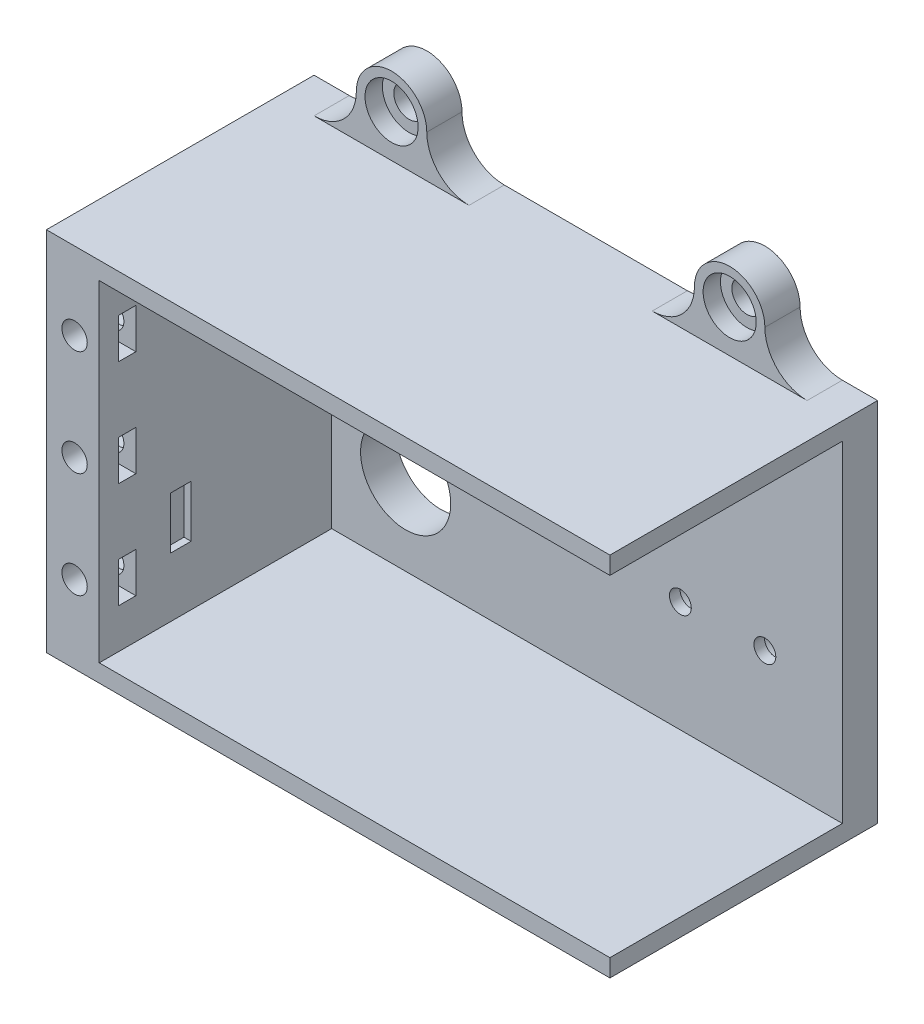
SolidWorks part; units mm, degrees
material "ABS"
ref_plane "Plan de face" through (0, 0, 0) normal (0, 0, 1) x (1, 0, 0)
ref_plane "Plan de dessus" through (0, 0, 0) normal (0, 1, 0) x (1, 0, 0)
ref_plane "Plan de droite" through (0, 0, 0) normal (1, 0, 0) x (0, 0, -1)
sketch "Esquisse3" plane through (0, 0, 0) normal (0, 0, 1) x (1, 0, 0)
  line L1 (-40, -26) -> (40, -26)
  line L2 (-40, -26) -> (-40, 26)
  line L3 (-40, 26) -> (40, 26)
  line L4 (40, -26) -> (40, 26)
  line L5 (-40, -26) -> (40, 26) construction
  line L6 (-40, 26) -> (40, -26) construction
  point P0 (0, 0)
  dimension "D1" = 80
  dimension "D2" = 52
extrude "Boss.-Extru.1" add sketch "Esquisse3" along normal blind 5 contours L3 L4 L1 L2
sketch "Esquisse4" plane through (0, 0, 5) normal (0, 0, 1) x (1, 0, 0)
  line L0 (-40, -26) -> (40, -26) construction
  line L1 (-40, -26) -> (-40, 26) construction
  circle A0 centre (-22, -12) radius 6.4
  dimension "D1" = 12.8
  dimension "D2" = 14
  dimension "D3" = 18
extrude "Enlèv. mat.-Extru.1" cut sketch "Esquisse4" against normal blind 10 contours A0
sketch "Esquisse5" plane through (0, 0, 5) normal (0, 0, 1) x (1, 0, 0)
  line L0 (40, -26) -> (40, 26) construction
  line L1 (-40, -26) -> (40, -26)
  line L3 (-32.5, -23.5) -> (40, -23.5)
  line L4 (40, -26) -> (40, -23.5)
  line L7 (-40, 26) -> (-40, -26)
  line L9 (-32.5, 23.5) -> (-32.5, -23.5)
  line L10 (-40, 26) -> (40, 26)
  line L12 (-32.5, 23.5) -> (40, 23.5)
  line L13 (40, 26) -> (40, 23.5)
  dimension "D1" = 7.5
  dimension "D2" = 2.5
  dimension "D3" = 2.5
extrude "Boss.-Extru.2" add sketch "Esquisse5" along normal blind 33
hole_wizard "Chambrage pour vis à tête ronde bombée M2.51" positions "Esquisse9" profile "Esquisse10" counterbore size "M2.5" standard "Ansi Metric" end condition up to next
sketch "Esquisse9" plane through (0, 0, 0) normal (0, 0, -1) x (-1, 0, 0)
  line L0 (40, 26) -> (-40, 26) construction
  line L1 (-40, -26) -> (-40, 26) construction
  point P0 (-17, 16.25)
  dimension "D1" = 9.75
  dimension "D2" = 23
sketch "Esquisse10" plane through (17, 16.25, 0) normal (1, 0, 0) x (0, 1, 0)
  line L0 (0, 0) -> (0, 5)
  line L1 (0, 5) -> (1.55, 5)
  line L3 (1.55, 5) -> (1.55, 3.5)
  line L4 (1.55, 3.5) -> (3, 3.5)
  line L5 (3, 3.5) -> (3, 0)
  line L7 (3, 0) -> (0, 0)
  line L11 (0, -6.35) -> (0, 107.95) construction
  dimension "Diamètre du perçage jusqu'au prochain" = 3.1
  dimension "Profondeur du perçage jusqu'au prochain" = 5
  dimension "Diamètre du chambrage" = 6
  dimension "Profondeur du chambrage" = 3.5
pattern_linear "Répétition linéaire1" count 2 spacing 12 along (1, 0, 0) count 2 spacing 24 along (0, -1, 0) of "Chambrage pour vis à tête ronde bombée M2.51"
sketch "Esquisse11" plane through (-40, 0, 0) normal (-1, 0, 0) x (0, 0, 1)
  line L0 (38, 26) -> (38, -26) construction
  line L1 (35.3, 17.85) -> (32.8, 17.85)
  line L2 (35.3, 17.85) -> (35.3, 12.15)
  line L3 (35.3, 12.15) -> (32.8, 12.15)
  line L4 (32.8, 17.85) -> (32.8, 12.15)
  line L14 (36.4917, 15) -> (30.8768, 15) construction
  line L15 (38, 26) -> (0, 26) construction
  dimension "D1" = 2.7
  dimension "D2" = 2.5
  dimension "D3" = 5.7
  dimension "D4" = 11
  dimension "D5" = 2.85
extrude "Enlèv. mat.-Extru.2" cut sketch "Esquisse11" against normal up to next
pattern_linear "Répétition linéaire2" count 3 spacing 15 along (0, -1, 0) of "Enlèv. mat.-Extru.2"
hole_wizard "Dégagement M31" positions "Esquisse13" profile "Esquisse15" hole size "M3" standard "Ansi Metric"
sketch "Esquisse13" plane through (0, 0, 38) normal (0, 0, 1) x (1, 0, 0)
  point P0 (-36, 15)
sketch "Esquisse15" plane through (-36, 15, 38) normal (1, 0, 0) x (0, -1, 0)
  line L0 (0, 0) -> (0, 7.4315)
  line L1 (0, 7.4315) -> (1.8, 6.35)
  line L2 (1.8, 6.35) -> (1.8, 0)
  line L5 (1.8, 0) -> (0, 0)
  line L10 (0, 7.4315) -> (-1.8, 6.35) construction
  line L11 (0, -6.35) -> (0, 107.95) construction
  dimension "Diamètre du perçage" = 3.6
  dimension "Profondeur du perçage" = 6.35
  dimension "Angle de pointe" = 118
pattern_linear "Répétition linéaire3" count 3 spacing 15 along (0, -1, 0) of "Dégagement M31"
sketch "Esquisse16" plane through (0, 0, 0) normal (0, 0, -1) x (-1, 0, 0)
  line L0 (-24, 52.4996) -> (-24, -58.7547) construction
  line L1 (24, 64.8334) -> (24, -50.5694) construction
  line L2 (40, 26) -> (-40, 26) construction
  line L3 (40, -26) -> (-40, -26) construction
  line L4 (-40, -26) -> (-40, 26) construction
  line L5 (40, -26) -> (40, 26) construction
  line L6 (-35, 26) -> (-13, 26)
  line L7 (13, 26) -> (35, 26)
  line L8 (-35, -26) -> (-13, -26)
  line L9 (13, -26) -> (35, -26)
  arc A0 (-19, 32) -> (-29, 32) centre (-24, 32) ccw
  arc A1 (-29, 32) -> (-35, 26) centre (-35, 32) cw
  arc A2 (-19, 32) -> (-13, 26) centre (-13, 32) ccw
  arc A3 (19, 32) -> (29, 32) centre (24, 32) cw
  arc A4 (29, 32) -> (35, 26) centre (35, 32) ccw
  arc A5 (19, 32) -> (13, 26) centre (13, 32) cw
  arc A6 (29, -32) -> (19, -32) centre (24, -32) cw
  arc A7 (29, -32) -> (35, -26) centre (35, -32) cw
  arc A8 (19, -32) -> (13, -26) centre (13, -32) ccw
  arc A9 (-19, -32) -> (-29, -32) centre (-24, -32) cw
  arc A10 (-19, -32) -> (-13, -26) centre (-13, -32) cw
  arc A11 (-29, -32) -> (-35, -26) centre (-35, -32) ccw
  dimension "D1" = 5
  dimension "D2" = 5
  dimension "D3" = 6
  dimension "D4" = 6
  dimension "D5" = 6
  dimension "D6" = 6
  dimension "D9" = 5
  dimension "D10" = 5
  dimension "D7" = 16
  dimension "D8" = 16
extrude "Boss.-Extru.3" add sketch "Esquisse16" against normal blind 5
hole_wizard "Chambrage pour vis à tête ronde bombée #61" positions "Esquisse17" profile "Esquisse18" counterbore size "#6" standard "Ansi Inch" end condition up to next
sketch "Esquisse17" plane through (0, 0, 5) normal (0, 0, 1) x (1, 0, 0)
  arc A0 (-29, -32) -> (-19, -32) centre (-24, -32) ccw construction
  arc A1 (19, -32) -> (29, -32) centre (24, -32) ccw construction
  arc A2 (29, 32) -> (19, 32) centre (24, 32) ccw construction
  arc A3 (-19, 32) -> (-29, 32) centre (-24, 32) ccw construction
  point P0 (-24, 32)
  point P2 (24, 32)
  point P4 (24, -32)
  point P6 (-24, -32)
  point P9 (0, 0)
  point P13 (0, 0)
  point P17 (0, 0)
  point P21 (0, 0)
sketch "Esquisse18" plane through (-24, 32, 5) normal (1, 0, 0) x (0, -1, 0)
  line L0 (0, 0) -> (0, 5)
  line L1 (0, 5) -> (2.1526, 5)
  line L3 (2.1526, 5) -> (2.1526, 2.4638)
  line L4 (2.1526, 2.4638) -> (3.7706, 2.4638)
  line L5 (3.7706, 2.4638) -> (3.7706, 0)
  line L7 (3.7706, 0) -> (0, 0)
  line L11 (0, -6.35) -> (0, 107.95) construction
  dimension "Diamètre du perçage jusqu'au prochain" = 4.3053
  dimension "Profondeur du perçage jusqu'au prochain" = 5
  dimension "Diamètre du chambrage" = 7.5413
  dimension "Profondeur du chambrage" = 2.4638
sketch "Esquisse19" plane through (-32.5, 0, 0) normal (1, 0, 0) x (0, 0, -1)
  line L1 (-24.9628, -15.0709) -> (-27.9144, -15.0709)
  line L2 (-24.9628, -15.0709) -> (-24.9628, -7.6874)
  line L3 (-24.9628, -7.6874) -> (-27.9144, -7.6874)
  line L4 (-27.9144, -15.0709) -> (-27.9144, -7.6874)
extrude "Enlèv. mat.-Extru.3" cut sketch "Esquisse19" against normal blind 1
